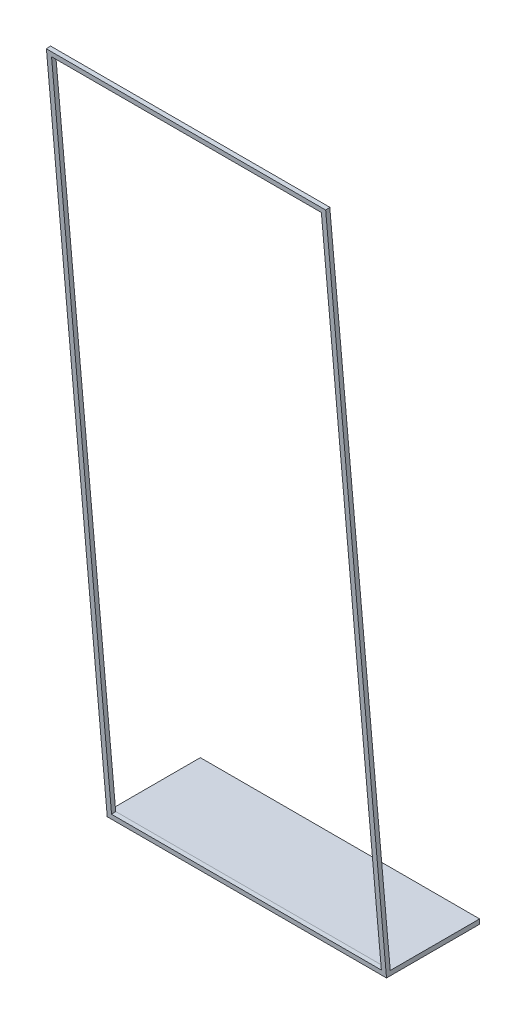
SolidWorks part; units mm, degrees
ref_plane "Front Plane" through (0, 0, 0) normal (0, 0, 1) x (1, 0, 0)
ref_plane "Top Plane" through (0, 0, 0) normal (0, 1, 0) x (1, 0, 0)
ref_plane "Right Plane" through (0, 0, 0) normal (1, 0, 0) x (0, 0, -1)
sketch "Sketch2" plane through (0, 0, 0) normal (0, 1, 0) x (1, 0, 0)
  line L1 (-3000, 2000) -> (3000, 2000)
  line L2 (-3000, 2000) -> (-3000, 0)
  line L3 (-3000, 0) -> (3000, 0)
  line L4 (3000, 2000) -> (3000, 0)
  dimension "D1" = 2000
  dimension "D2" = 6000
extrude "Boss-Extrude1" add sketch "Sketch2" along normal blind 100
sketch "Sketch3" plane through (0, 0, 0) normal (1, 0, 0) x (0, 0, -1)
  line L0 (0, 0) -> (-1307.3361, 14942.9205)
  line L1 (-1307.3361, 14942.9205) -> (-1218.7744, 14950.6686)
  line L2 (-1218.7744, 14950.6686) -> (89.2396, 0)
  line L3 (0, 0) -> (2000, 0) construction
  line L4 (89.2396, 0) -> (0, 0)
  line L5 (0, 100) -> (0, 0) construction
  dimension "D1" = 5
  dimension "D2" = 88.9
  dimension "D3" = 15000
extrude "Boss-Extrude2" add sketch "Sketch3" along normal through all and the other way through all
sketch "Sketch4" plane through (0, 0, 0) normal (0, -0.0872, 0.9962) x (1, 0, 0)
  line L0 (-3000, 0) -> (3000, 15000) construction
  line L1 (-2898.4, 14898.4) -> (2898.4, 14898.4)
  line L2 (-2898.4, 14898.4) -> (-2898.4, 101.6)
  line L3 (-2898.4, 101.6) -> (2898.4, 101.6)
  line L4 (2898.4, 14898.4) -> (2898.4, 101.6)
  line L5 (2898.4, 101.6) -> (-2898.4, 14898.4) construction
  line L6 (3000, 15000) -> (-3000, 15000) construction
  line L7 (-3000, 15000) -> (-3000, 0) construction
  point P8 (0, 7500)
  dimension "D1" = 101.6
  dimension "D2" = 101.6
extrude "Cut-Extrude1" cut sketch "Sketch4" against normal through all
